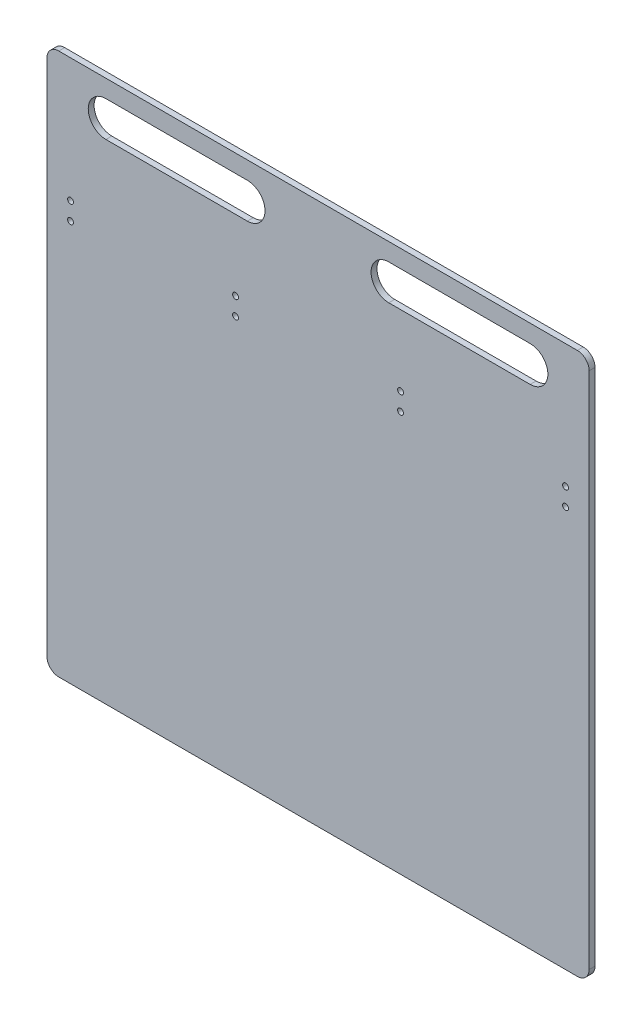
SolidWorks part; units mm, degrees
material "PC High Viscosity"
ref_plane "Front Plane" through (0, 0, 0) normal (0, 0, 1) x (1, 0, 0)
ref_plane "Top Plane" through (0, 0, 0) normal (0, 1, 0) x (1, 0, 0)
ref_plane "Right Plane" through (0, 0, 0) normal (1, 0, 0) x (0, 0, -1)
sketch "Sketch1" plane through (0, 0, 0) normal (0, 0, 1) x (1, 0, 0)
  line L0 (-228.6, 273.05) -> (-76.2, 273.05)
  line L1 (-292.1, -292.1) -> (292.1, -292.1)
  line L2 (-292.1, -292.1) -> (-292.1, 292.1)
  line L3 (-292.1, 292.1) -> (292.1, 292.1)
  line L4 (292.1, -292.1) -> (292.1, 292.1)
  line L5 (-292.1, -292.1) -> (292.1, 292.1) construction
  line L6 (-292.1, 292.1) -> (292.1, -292.1) construction
  line L7 (-228.6, 234.95) -> (-76.2, 234.95)
  line L8 (76.2, 273.05) -> (228.6, 273.05)
  line L9 (76.2, 234.95) -> (228.6, 234.95)
  arc A0 (-228.6, 273.05) -> (-228.6, 234.95) centre (-228.6, 254) ccw
  arc A1 (228.6, 234.95) -> (228.6, 273.05) centre (228.6, 254) ccw
  arc A2 (-76.2, 234.95) -> (-76.2, 273.05) centre (-76.2, 254) ccw
  arc A3 (76.2, 273.05) -> (76.2, 234.95) centre (76.2, 254) ccw
  circle A4 centre (-266.7, 139.7) radius 3.175
  circle A5 centre (-88.9, 139.7) radius 3.175
  circle A6 centre (88.9, 139.7) radius 3.175
  circle A7 centre (266.7, 139.7) radius 3.175
  circle A8 centre (-88.9, 158.75) radius 3.175
  circle A9 centre (88.9, 158.75) radius 3.175
  circle A10 centre (266.7, 158.75) radius 3.175
  circle A11 centre (-266.7, 158.75) radius 3.175
  point P0 (0, 0)
  dimension "D3" = 38.1
  dimension "D4" = 38.1
  dimension "D9" = 38.1
  dimension "D10" = 38.1
  dimension "D12" = 152.4
  dimension "D17" = 6.35
  dimension "D1" = 584.2
  dimension "D2" = 584.2
  dimension "D5" = 38.1
  dimension "D6" = 38.1
  dimension "D7" = 38.1
  dimension "D8" = 38.1
  dimension "D11" = 152.4
  dimension "D13" = 63.5
  dimension "D14" = 63.5
  dimension "D15" = 431.8
  dimension "D16" = 25.4
  dimension "D20" = 180
  dimension "D21" = 57.15
  dimension "D22" = 63.5
  dimension "D23" = 152.4
  dimension "D18" = 4
  dimension "D19" = 2
extrude "Boss-Extrude1" add sketch "Sketch1" along normal blind 6.35
fillet "Fillet1" radius 12.7 4 edges at (292.1, -292.1, 3.175) (-292.1, -292.1, 3.175) (-292.1, 292.1, 3.175) (292.1, 292.1, 3.175)
